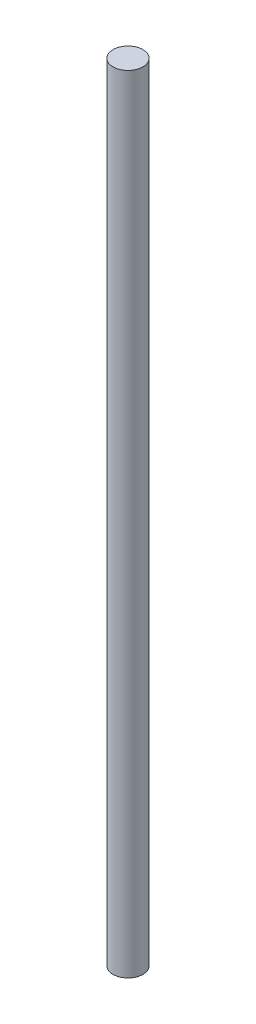
SolidWorks part; units mm, degrees
material "Plain Carbon Steel"
ref_plane "Front Plane" through (0, 0, 0) normal (0, 0, 1) x (1, 0, 0)
ref_plane "Top Plane" through (0, 0, 0) normal (0, 1, 0) x (1, 0, 0)
ref_plane "Right Plane" through (0, 0, 0) normal (1, 0, 0) x (0, 0, -1)
sketch "Sketch1" plane through (0, 0, 0) normal (0, 1, 0) x (1, 0, 0)
  circle A1 centre (0, 0) radius 4
  dimension "D2" = 8
extrude "Boss-Extrude1" add sketch "Sketch1" along normal mid plane 210
